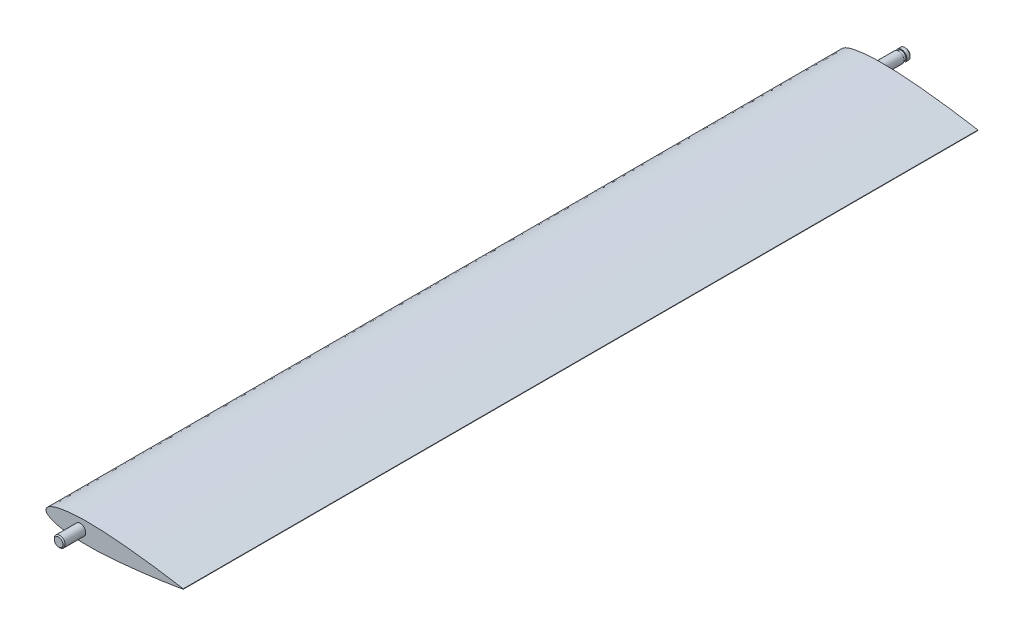
SolidWorks part; units mm, degrees
material "AISI Carbon Fiber"
ref_plane "Front Plane" through (0, 0, 0) normal (0, 0, 1) x (1, 0, 0)
ref_plane "Top Plane" through (0, 0, 0) normal (0, 1, 0) x (1, 0, 0)
ref_plane "Right Plane" through (0, 0, 0) normal (1, 0, 0) x (0, 0, -1)
curve "Curve1"
  spline degree 3 poles (38, 0.0599, 0) (37.987, 0.0621, 0) (37.935, 0.0712, 0) (37.8182, 0.0917, 0) (37.6241, 0.1254, 0) (37.3535, 0.1721, 0) (37.0074, 0.2313, 0) (36.5874, 0.3022, 0) (36.0951, 0.3842, 0) (35.5325, 0.4763, 0) (34.902, 0.5776, 0) (34.2062, 0.6871, 0) (33.4479, 0.8039, 0) (32.6302, 0.9268, 0) (31.7565, 1.0547, 0) (30.8304, 1.1867, 0) (29.8556, 1.3214, 0) (28.8363, 1.4579, 0) (27.7765, 1.595, 0) (26.6807, 1.7315, 0) (25.5533, 1.8661, 0) (24.399, 1.9977, 0) (23.2225, 2.125, 0) (22.0286, 2.2465, 0) (20.8224, 2.361, 0) (19.6086, 2.467, 0) (18.3923, 2.5631, 0) (17.1785, 2.6478, 0) (15.9721, 2.7198, 0) (14.7782, 2.7776, 0) (13.6016, 2.82, 0) (12.4472, 2.8458, 0) (11.3196, 2.8539, 0) (10.2236, 2.8435, 0) (9.1636, 2.8139, 0) (8.144, 2.7648, 0) (7.1689, 2.6959, 0) (6.2424, 2.6073, 0) (5.3682, 2.4992, 0) (4.55, 2.3724, 0) (3.7909, 2.2275, 0) (3.0942, 2.0654, 0) (2.4625, 1.8874, 0) (1.8984, 1.6945, 0) (1.4039, 1.4881, 0) (0.9808, 1.2692, 0) (0.6303, 1.0387, 0) (0.3535, 0.7969, 0) (0.1517, 0.5431, 0) (0.0276, 0.2761, 0) (-0.0134, 0, 0) (0.0276, -0.2761, 0) (0.1517, -0.5431, 0) (0.3535, -0.7969, 0) (0.6303, -1.0387, 0) (0.9808, -1.2692, 0) (1.4039, -1.4881, 0) (1.8984, -1.6945, 0) (2.4625, -1.8874, 0) (3.0942, -2.0654, 0) (3.7909, -2.2275, 0) (4.55, -2.3724, 0) (5.3682, -2.4992, 0) (6.2424, -2.6073, 0) (7.1689, -2.6959, 0) (8.144, -2.7648, 0) (9.1636, -2.8139, 0) (10.2236, -2.8435, 0) (11.3196, -2.8539, 0) (12.4472, -2.8458, 0) (13.6016, -2.82, 0) (14.7782, -2.7776, 0) (15.9721, -2.7198, 0) (17.1785, -2.6478, 0) (18.3923, -2.5631, 0) (19.6086, -2.467, 0) (20.8224, -2.361, 0) (22.0286, -2.2465, 0) (23.2225, -2.125, 0) (24.399, -1.9977, 0) (25.5533, -1.8661, 0) (26.6807, -1.7315, 0) (27.7765, -1.595, 0) (28.8363, -1.4579, 0) (29.8556, -1.3214, 0) (30.8304, -1.1867, 0) (31.7565, -1.0547, 0) (32.6302, -0.9268, 0) (33.4479, -0.8039, 0) (34.2062, -0.6871, 0) (34.902, -0.5776, 0) (35.5325, -0.4763, 0) (36.0951, -0.3842, 0) (36.5874, -0.3022, 0) (37.0074, -0.2313, 0) (37.3535, -0.1721, 0) (37.6241, -0.1254, 0) (37.8182, -0.0917, 0) (37.935, -0.0712, 0) (37.987, -0.0621, 0) (38, -0.0599, 0) knots 0 0 0 0 0.000507 0.002027 0.004551 0.008071 0.01257 0.018029 0.024425 0.031731 0.039914 0.048941 0.058774 0.06937 0.080686 0.092674 0.105284 0.118464 0.132158 0.146309 0.160859 0.175747 0.190912 0.20629 0.221818 0.237431 0.253066 0.268658 0.284144 0.299461 0.314547 0.329343 0.343791 0.357834 0.37142 0.384499 0.397022 0.408945 0.420228 0.430833 0.440729 0.449888 0.458288 0.465915 0.472763 0.478842 0.484178 0.488829 0.492895 0.49654 0.5 0.50346 0.507105 0.511171 0.515822 0.521158 0.527237 0.534085 0.541712 0.550112 0.559271 0.569167 0.579772 0.591055 0.602978 0.615501 0.62858 0.642166 0.656209 0.670657 0.685453 0.700539 0.715856 0.731342 0.746934 0.762569 0.778182 0.79371 0.809088 0.824253 0.839141 0.853691 0.867842 0.881536 0.894716 0.907326 0.919314 0.93063 0.941226 0.951059 0.960086 0.968269 0.975575 0.981971 0.98743 0.991929 0.995449 0.997973 0.999493 1 1 1 1
sketch3d "3DSketch1"
  line L0 (0, 0, 0) -> (38, 0, 0) construction
  line L1 (9.5, -5.7646, 0) -> (9.5, 5.7646, 0) construction
  line L2 (38, 0.0599, 0) -> (38, -0.0599, 0)
  spline S0 degree 3 poles (604.1581, 2945.7624, 0) (69.9098, -7.9846, 0) (54.106, -2.7558, 0) (37.1208, 0.2136, 0) (35.8767, 0.4227, 0) (34.1443, 0.698, 0) (32.8836, 0.8897, 0) (31.7565, 1.0547, 0) (30.8304, 1.1867, 0) (29.8556, 1.3214, 0) (28.8363, 1.4579, 0) (27.7765, 1.595, 0) (26.6807, 1.7315, 0) (25.5533, 1.8661, 0) (24.399, 1.9977, 0) (23.2225, 2.125, 0) (22.0286, 2.2465, 0) (20.8224, 2.361, 0) (19.6086, 2.467, 0) (18.3923, 2.5631, 0) (17.1785, 2.6478, 0) (15.9721, 2.7198, 0) (14.7782, 2.7776, 0) (13.6016, 2.82, 0) (12.4472, 2.8458, 0) (11.3196, 2.8539, 0) (10.2236, 2.8435, 0) (9.1636, 2.8139, 0) (8.144, 2.7648, 0) (7.1689, 2.6959, 0) (6.2424, 2.6073, 0) (5.3682, 2.4992, 0) (4.55, 2.3724, 0) (3.7909, 2.2275, 0) (3.0942, 2.0654, 0) (2.4625, 1.8874, 0) (1.8984, 1.6945, 0) (1.4039, 1.4881, 0) (0.9808, 1.2692, 0) (0.6303, 1.0387, 0) (0.3535, 0.7969, 0) (0.1517, 0.5431, 0) (0.0276, 0.2761, 0) (-0.0134, 0, 0) (0.0276, -0.2761, 0) (0.1517, -0.5431, 0) (0.3535, -0.7969, 0) (0.6303, -1.0387, 0) (0.9808, -1.2692, 0) (1.4039, -1.4881, 0) (1.8984, -1.6945, 0) (2.4625, -1.8874, 0) (3.0942, -2.0654, 0) (3.7909, -2.2275, 0) (4.55, -2.3724, 0) (5.3682, -2.4992, 0) (6.2424, -2.6073, 0) (7.1689, -2.6959, 0) (8.144, -2.7648, 0) (9.1636, -2.8139, 0) (10.2236, -2.8435, 0) (11.3196, -2.8539, 0) (12.4472, -2.8458, 0) (13.6016, -2.82, 0) (14.7782, -2.7776, 0) (15.9721, -2.7198, 0) (17.1785, -2.6478, 0) (18.3923, -2.5631, 0) (19.6086, -2.467, 0) (20.8224, -2.361, 0) (22.0286, -2.2465, 0) (23.2225, -2.125, 0) (24.399, -1.9977, 0) (25.5533, -1.8661, 0) (26.6807, -1.7315, 0) (27.7765, -1.595, 0) (28.8363, -1.4579, 0) (29.8556, -1.3214, 0) (30.8304, -1.1867, 0) (32.0297, -1.0158, 0) (33.3891, -0.8142, 0) (34.8372, -0.589, 0) (36.1409, -0.3777, 0) (37.0492, -0.2247, 0) (37.6241, -0.1254, 0) (37.8182, -0.0917, 0) (54.1059, 2.7557, 0) (69.9096, 7.9845, 0) (604.1475, -2945.7032, 0) knots -0.630247 -0.630247 -0.630247 -0.630247 0.000507 0.002027 0.031731 0.048941 0.06937 0.080686 0.092674 0.105284 0.118464 0.132158 0.146309 0.160859 0.175747 0.190912 0.20629 0.221818 0.237431 0.253066 0.268658 0.284144 0.299461 0.314547 0.329343 0.343791 0.357834 0.37142 0.384499 0.397022 0.408945 0.420228 0.430833 0.440729 0.449888 0.458288 0.465915 0.472763 0.478842 0.484178 0.488829 0.492895 0.49654 0.5 0.50346 0.507105 0.511171 0.515822 0.521158 0.527237 0.534085 0.541712 0.550112 0.559271 0.569167 0.579772 0.591055 0.602978 0.615501 0.62858 0.642166 0.656209 0.670657 0.685453 0.700539 0.715856 0.731342 0.746934 0.762569 0.778182 0.79371 0.809088 0.824253 0.839141 0.853691 0.867842 0.881536 0.894716 0.907326 0.919314 0.941226 0.960086 0.975575 0.991929 0.995449 0.997973 0.999493 1.630243 1.630243 1.630243 1.630243 only from (38, 0.0599, 0) to (38, -0.0599, 0) construction
  spline S1 degree 3 poles (38, 0.0599, 0) (37.987, 0.0621, 0) (37.935, 0.0712, 0) (37.1208, 0.2136, 0) (35.8767, 0.4227, 0) (34.1443, 0.698, 0) (32.8836, 0.8897, 0) (31.7565, 1.0547, 0) (30.8304, 1.1867, 0) (29.8556, 1.3214, 0) (28.8363, 1.4579, 0) (27.7765, 1.595, 0) (26.6807, 1.7315, 0) (25.5533, 1.8661, 0) (24.399, 1.9977, 0) (23.2225, 2.125, 0) (22.0286, 2.2465, 0) (20.8224, 2.361, 0) (19.6086, 2.467, 0) (18.3923, 2.5631, 0) (17.1785, 2.6478, 0) (15.9721, 2.7198, 0) (14.7782, 2.7776, 0) (13.6016, 2.82, 0) (12.4472, 2.8458, 0) (11.3196, 2.8539, 0) (10.2236, 2.8435, 0) (9.1636, 2.8139, 0) (8.144, 2.7648, 0) (7.1689, 2.6959, 0) (6.2424, 2.6073, 0) (5.3682, 2.4992, 0) (4.55, 2.3724, 0) (3.7909, 2.2275, 0) (3.0942, 2.0654, 0) (2.4625, 1.8874, 0) (1.8984, 1.6945, 0) (1.4039, 1.4881, 0) (0.9808, 1.2692, 0) (0.6303, 1.0387, 0) (0.3535, 0.7969, 0) (0.1517, 0.5431, 0) (0.0276, 0.2761, 0) (-0.0134, 0, 0) (0.0276, -0.2761, 0) (0.1517, -0.5431, 0) (0.3535, -0.7969, 0) (0.6303, -1.0387, 0) (0.9808, -1.2692, 0) (1.4039, -1.4881, 0) (1.8984, -1.6945, 0) (2.4625, -1.8874, 0) (3.0942, -2.0654, 0) (3.7909, -2.2275, 0) (4.55, -2.3724, 0) (5.3682, -2.4992, 0) (6.2424, -2.6073, 0) (7.1689, -2.6959, 0) (8.144, -2.7648, 0) (9.1636, -2.8139, 0) (10.2236, -2.8435, 0) (11.3196, -2.8539, 0) (12.4472, -2.8458, 0) (13.6016, -2.82, 0) (14.7782, -2.7776, 0) (15.9721, -2.7198, 0) (17.1785, -2.6478, 0) (18.3923, -2.5631, 0) (19.6086, -2.467, 0) (20.8224, -2.361, 0) (22.0286, -2.2465, 0) (23.2225, -2.125, 0) (24.399, -1.9977, 0) (25.5533, -1.8661, 0) (26.6807, -1.7315, 0) (27.7765, -1.595, 0) (28.8363, -1.4579, 0) (29.8556, -1.3214, 0) (30.8304, -1.1867, 0) (32.0297, -1.0158, 0) (33.3891, -0.8142, 0) (34.8372, -0.589, 0) (36.1409, -0.3777, 0) (37.0492, -0.2247, 0) (37.6241, -0.1254, 0) (37.8182, -0.0917, 0) (37.935, -0.0712, 0) (37.987, -0.0621, 0) (38, -0.0599, 0) knots 0 0 0 0 0.000507 0.002027 0.031731 0.048941 0.06937 0.080686 0.092674 0.105284 0.118464 0.132158 0.146309 0.160859 0.175747 0.190912 0.20629 0.221818 0.237431 0.253066 0.268658 0.284144 0.299461 0.314547 0.329343 0.343791 0.357834 0.37142 0.384499 0.397022 0.408945 0.420228 0.430833 0.440729 0.449888 0.458288 0.465915 0.472763 0.478842 0.484178 0.488829 0.492895 0.49654 0.5 0.50346 0.507105 0.511171 0.515822 0.521158 0.527237 0.534085 0.541712 0.550112 0.559271 0.569167 0.579772 0.591055 0.602978 0.615501 0.62858 0.642166 0.656209 0.670657 0.685453 0.700539 0.715856 0.731342 0.746934 0.762569 0.778182 0.79371 0.809088 0.824253 0.839141 0.853691 0.867842 0.881536 0.894716 0.907326 0.919314 0.941226 0.960086 0.975575 0.991929 0.995449 0.997973 0.999493 1 1 1 1
  point P8 (9.5, 0, 0)
  dimension "D1" = 0.1197
extrude "Boss-Extrude1" add sketch "3DSketch1" along direction (0, 0, 1) on the side of the normal blind 220
curve "Curve6"
  spline degree 3 poles (0.8371, 0.1076, 0) (0.8458, 0.1212, 0) (0.8686, 0.1567, 0) (0.9123, 0.2091, 0) (0.9749, 0.2742, 0) (1.0496, 0.3405, 0) (1.148, 0.4173, 0) (1.2564, 0.4919, 0) (1.3911, 0.5748, 0) (1.5328, 0.6532, 0) (1.7028, 0.7383, 0) (1.8766, 0.8172, 0) (2.0803, 0.9017, 0) (2.3018, 0.9855, 0) (2.5379, 1.0666, 0) (2.7908, 1.1464, 0) (3.0397, 1.2184, 0) (3.3223, 1.2936, 0) (3.598, 1.3609, 0) (3.9088, 1.4305, 0) (4.21, 1.4924, 0) (4.5476, 1.5559, 0) (4.8731, 1.6117, 0) (5.236, 1.6684, 0) (5.6124, 1.7217, 0) (5.9994, 1.7707, 0) (6.399, 1.8161, 0) (6.7803, 1.8548, 0) (7.2016, 1.8926, 0) (7.6023, 1.9241, 0) (8.0438, 1.9542, 0) (8.4627, 1.9784, 0) (8.9229, 2.0006, 0) (9.3583, 2.0176, 0) (9.8356, 2.032, 0) (10.3217, 2.0426, 0) (10.8145, 2.0489, 0) (11.3152, 2.0514, 0) (11.7864, 2.0503, 0) (12.3, 2.0454, 0) (12.7823, 2.0376, 0) (13.3071, 2.0257, 0) (13.7991, 2.0114, 0) (14.3334, 1.9928, 0) (14.8333, 1.9726, 0) (15.3753, 1.9476, 0) (15.9208, 1.9197, 0) (16.4687, 1.8886, 0) (17.0192, 1.8548, 0) (17.532, 1.8209, 0) (18.0855, 1.782, 0) (18.6004, 1.7436, 0) (19.1552, 1.7001, 0) (19.6704, 1.6577, 0) (20.2247, 1.6101, 0) (20.7386, 1.5641, 0) (21.2905, 1.5129, 0) (21.8404, 1.4601, 0) (22.3882, 1.4056, 0) (22.933, 1.3499, 0) (23.4358, 1.2969, 0) (23.9736, 1.2389, 0) (24.4692, 1.184, 0) (24.9983, 1.1241, 0) (25.485, 1.0678, 0) (26.0037, 1.0066, 0) (26.4799, 0.9493, 0) (26.9865, 0.8871, 0) (27.4857, 0.8248, 0) (27.9785, 0.762, 0) (28.463, 0.6994, 0) (28.9056, 0.6412, 0) (29.3739, 0.5787, 0) (29.8006, 0.5209, 0) (30.2512, 0.4591, 0) (30.6608, 0.4021, 0) (31.0922, 0.3412, 0) (31.4833, 0.2853, 0) (31.8941, 0.2259, 0) (32.2929, 0.1676, 0) (32.5742, 0.1257, 0) (32.7126, 0.1052, 0) knots 0 0 0 0 0.001498 0.003915 0.006305 0.009868 0.013175 0.01787 0.022065 0.027843 0.032883 0.039693 0.045539 0.053333 0.061655 0.068685 0.077928 0.085679 0.095804 0.104247 0.115218 0.124322 0.136103 0.145839 0.158391 0.171355 0.182014 0.195688 0.2069 0.221242 0.232971 0.24794 0.260151 0.275699 0.288356 0.304436 0.320791 0.334062 0.350872 0.364486 0.381697 0.395612 0.413171 0.427341 0.445193 0.459574 0.477661 0.495853 0.51047 0.528806 0.543514 0.561934 0.576686 0.59513 0.609876 0.628283 0.642977 0.661287 0.679517 0.694031 0.712071 0.726408 0.744198 0.758312 0.775793 0.789637 0.806751 0.82028 0.836971 0.853405 0.866354 0.88228 0.894802 0.910169 0.922223 0.936979 0.948526 0.962623 0.973625 0.987018 1 1 1 1
curve "Curve7"
  spline degree 3 poles (0.8371, -0.1076, 0) (0.8458, -0.1212, 0) (0.8686, -0.1567, 0) (0.9123, -0.2091, 0) (0.9749, -0.2742, 0) (1.0496, -0.3405, 0) (1.148, -0.4173, 0) (1.2564, -0.4919, 0) (1.3911, -0.5748, 0) (1.5328, -0.6532, 0) (1.7028, -0.7383, 0) (1.8766, -0.8172, 0) (2.0803, -0.9017, 0) (2.3018, -0.9855, 0) (2.5379, -1.0666, 0) (2.7908, -1.1464, 0) (3.0397, -1.2184, 0) (3.3223, -1.2936, 0) (3.598, -1.3609, 0) (3.9088, -1.4305, 0) (4.21, -1.4924, 0) (4.5476, -1.5559, 0) (4.8731, -1.6117, 0) (5.236, -1.6684, 0) (5.6124, -1.7217, 0) (5.9994, -1.7707, 0) (6.399, -1.8161, 0) (6.7803, -1.8548, 0) (7.2016, -1.8926, 0) (7.6023, -1.9241, 0) (8.0438, -1.9542, 0) (8.4627, -1.9784, 0) (8.9229, -2.0006, 0) (9.3583, -2.0176, 0) (9.8356, -2.032, 0) (10.3217, -2.0426, 0) (10.8145, -2.0489, 0) (11.3152, -2.0514, 0) (11.7864, -2.0503, 0) (12.3, -2.0454, 0) (12.7823, -2.0376, 0) (13.3071, -2.0257, 0) (13.7991, -2.0114, 0) (14.3334, -1.9928, 0) (14.8333, -1.9726, 0) (15.3753, -1.9476, 0) (15.9208, -1.9197, 0) (16.4687, -1.8886, 0) (17.0192, -1.8548, 0) (17.532, -1.8209, 0) (18.0855, -1.782, 0) (18.6004, -1.7436, 0) (19.1552, -1.7001, 0) (19.6704, -1.6577, 0) (20.2247, -1.6101, 0) (20.7386, -1.5641, 0) (21.2905, -1.5129, 0) (21.8404, -1.4601, 0) (22.3882, -1.4056, 0) (22.933, -1.3499, 0) (23.4358, -1.2969, 0) (23.9736, -1.2389, 0) (24.4692, -1.184, 0) (24.9983, -1.1241, 0) (25.485, -1.0678, 0) (26.0037, -1.0066, 0) (26.4799, -0.9493, 0) (26.9865, -0.8871, 0) (27.4857, -0.8248, 0) (27.9785, -0.762, 0) (28.463, -0.6994, 0) (28.9056, -0.6412, 0) (29.3739, -0.5787, 0) (29.8006, -0.5209, 0) (30.2512, -0.4591, 0) (30.6608, -0.4021, 0) (31.0922, -0.3412, 0) (31.4833, -0.2853, 0) (31.8941, -0.2259, 0) (32.2929, -0.1676, 0) (32.5742, -0.1257, 0) (32.7126, -0.1052, 0) knots 0 0 0 0 0.001498 0.003915 0.006305 0.009868 0.013175 0.01787 0.022065 0.027843 0.032883 0.039693 0.045539 0.053333 0.061655 0.068685 0.077928 0.085679 0.095804 0.104247 0.115218 0.124322 0.136103 0.145839 0.158391 0.171355 0.182014 0.195688 0.2069 0.221242 0.232971 0.24794 0.260151 0.275699 0.288356 0.304436 0.320791 0.334062 0.350872 0.364486 0.381697 0.395612 0.413171 0.427341 0.445193 0.459574 0.477661 0.495853 0.51047 0.528806 0.543514 0.561934 0.576686 0.59513 0.609876 0.628283 0.642977 0.661287 0.679517 0.694031 0.712071 0.726408 0.744198 0.758312 0.775793 0.789637 0.806751 0.82028 0.836971 0.853405 0.866354 0.88228 0.894802 0.910169 0.922223 0.936979 0.948526 0.962623 0.973625 0.987018 1 1 1 1
sketch "Sketch5" plane through (0, 0, 0) normal (0, 0, -1) x (-1, 0, 0)
  line L0 (-32.7126, 0.1052) -> (-32.7126, -0.1052)
  line L1 (-38, 0.0599) -> (-38, -0.0599)
  line L2 (-38, 0.0599) -> (-38, -0.0599)
  line L3 (-0.8371, 0.1076) -> (-0.8371, -0.1076)
  spline S0 degree 3 poles (4087.6061, -2873.0002) (-19.499, 20.4027) (1.0641, 2.163) (-0.9123, -0.2091) (-0.9749, -0.2742) (-1.0496, -0.3405) (-1.148, -0.4173) (-1.2564, -0.4919) (-1.3911, -0.5748) (-1.5328, -0.6532) (-1.7028, -0.7383) (-1.8766, -0.8172) (-2.0803, -0.9017) (-2.3018, -0.9855) (-2.5379, -1.0666) (-2.7908, -1.1464) (-3.0397, -1.2184) (-3.3223, -1.2936) (-3.598, -1.3609) (-3.9088, -1.4305) (-4.21, -1.4924) (-4.5476, -1.5559) (-4.8731, -1.6117) (-5.236, -1.6684) (-5.6124, -1.7217) (-5.9994, -1.7707) (-6.399, -1.8161) (-6.7803, -1.8548) (-7.2016, -1.8926) (-7.6023, -1.9241) (-8.0438, -1.9542) (-8.6301, -1.9881) (-9.2267, -2.0137) (-10.0119, -2.0374) (-10.6411, -2.048) (-11.462, -2.0521) (-12.2688, -2.0475) (-13.2744, -2.0281) (-14.2992, -1.9956) (-15.1831, -1.9575) (-16.0782, -1.9116) (-16.9818, -1.8584) (-18.0471, -1.7859) (-19.1158, -1.7043) (-20.1845, -1.6145) (-21.2887, -1.5141) (-22.5393, -1.3918) (-23.7761, -1.2615) (-24.9561, -1.1296) (-26.1402, -0.9913) (-27.4669, -0.8286) (-28.8848, -0.6452) (-30.0767, -0.4838) (-30.9347, -0.3637) (-31.4833, -0.2853) (-31.8941, -0.2259) (-75.5916, 6.1667) (-116.8044, 28.5604) (-893.0755, -4923.7281) knots -0.279234 -0.279234 -0.279234 -0.279234 0.001498 0.003915 0.006305 0.009868 0.013175 0.01787 0.022065 0.027843 0.032883 0.039693 0.045539 0.053333 0.061655 0.068685 0.077928 0.085679 0.095804 0.104247 0.115218 0.124322 0.136103 0.145839 0.158391 0.171355 0.182014 0.195688 0.2069 0.221242 0.232971 0.24794 0.275699 0.288356 0.320791 0.334062 0.364486 0.395612 0.427341 0.459574 0.477661 0.51047 0.543514 0.576686 0.609876 0.642977 0.679517 0.726408 0.758312 0.789637 0.836971 0.88228 0.922223 0.948526 0.962623 0.973625 0.987018 5.058378 5.058378 5.058378 5.058378 only from (-0.8371, -0.1076) to (-32.7126, -0.1052) construction
  spline S1 degree 3 poles (-1134.4373, -5897.8795) (-78.0711, 10.8547) (-58.3094, 3.4906) (-37.8182, -0.0917) (-37.6241, -0.1254) (-37.0492, -0.2247) (-36.1409, -0.3777) (-34.8372, -0.589) (-33.3891, -0.8142) (-32.0297, -1.0158) (-30.8304, -1.1867) (-29.8556, -1.3214) (-28.8363, -1.4579) (-27.7765, -1.595) (-26.6807, -1.7315) (-25.5533, -1.8661) (-24.399, -1.9977) (-23.2225, -2.125) (-22.0286, -2.2465) (-20.8224, -2.361) (-19.6086, -2.467) (-18.3923, -2.5631) (-17.1785, -2.6478) (-15.9721, -2.7198) (-14.7782, -2.7776) (-13.6016, -2.82) (-12.4472, -2.8458) (-11.3196, -2.8539) (-10.2236, -2.8435) (-9.1636, -2.8139) (-8.144, -2.7648) (-7.1689, -2.6959) (-6.2424, -2.6073) (-5.3682, -2.4992) (-4.55, -2.3724) (-3.7909, -2.2275) (-3.0942, -2.0654) (-2.4625, -1.8874) (-1.8984, -1.6945) (-1.4039, -1.4881) (-0.9808, -1.2692) (-0.6303, -1.0387) (-0.3535, -0.7969) (-0.1517, -0.5431) (-0.0276, -0.2761) (0.0134, 0) (-0.0276, 0.2761) (-0.1517, 0.5431) (-0.3535, 0.7969) (-0.6303, 1.0387) (-0.9808, 1.2692) (-1.4039, 1.4881) (-1.8984, 1.6945) (-2.4625, 1.8874) (-3.0942, 2.0654) (-3.7909, 2.2275) (-4.55, 2.3724) (-5.3682, 2.4992) (-6.2424, 2.6073) (-7.1689, 2.6959) (-8.144, 2.7648) (-9.1636, 2.8139) (-10.2236, 2.8435) (-11.3196, 2.8539) (-12.4472, 2.8458) (-13.6016, 2.82) (-14.7782, 2.7776) (-15.9721, 2.7198) (-17.1785, 2.6478) (-18.3923, 2.5631) (-19.6086, 2.467) (-20.8224, 2.361) (-22.0286, 2.2465) (-23.2225, 2.125) (-24.399, 1.9977) (-25.5533, 1.8661) (-26.6807, 1.7315) (-27.7765, 1.595) (-28.8363, 1.4579) (-29.8556, 1.3214) (-30.8304, 1.1867) (-31.7565, 1.0547) (-32.8836, 0.8897) (-34.1443, 0.698) (-35.8767, 0.4227) (-37.1208, 0.2136) (-58.3096, -3.4906) (-78.0715, -10.8549) (-1134.4729, 5898.0786) knots -0.794067 -0.794067 -0.794067 -0.794067 0.000507 0.002027 0.004551 0.008071 0.024425 0.039914 0.058774 0.080686 0.092674 0.105284 0.118464 0.132158 0.146309 0.160859 0.175747 0.190912 0.20629 0.221818 0.237431 0.253066 0.268658 0.284144 0.299461 0.314547 0.329343 0.343791 0.357834 0.37142 0.384499 0.397022 0.408945 0.420228 0.430833 0.440729 0.449888 0.458288 0.465915 0.472763 0.478842 0.484178 0.488829 0.492895 0.49654 0.5 0.50346 0.507105 0.511171 0.515822 0.521158 0.527237 0.534085 0.541712 0.550112 0.559271 0.569167 0.579772 0.591055 0.602978 0.615501 0.62858 0.642166 0.656209 0.670657 0.685453 0.700539 0.715856 0.731342 0.746934 0.762569 0.778182 0.79371 0.809088 0.824253 0.839141 0.853691 0.867842 0.881536 0.894716 0.907326 0.919314 0.93063 0.951059 0.968269 0.997973 0.999493 1.794076 1.794076 1.794076 1.794076 only from (-38, -0.0599) to (-38, 0.0599)
  spline S2 degree 3 poles (-38, -0.0599) (-37.987, -0.0621) (-37.935, -0.0712) (-37.8182, -0.0917) (-37.6241, -0.1254) (-37.0492, -0.2247) (-36.1409, -0.3777) (-34.8372, -0.589) (-33.3891, -0.8142) (-32.0297, -1.0158) (-30.8304, -1.1867) (-29.8556, -1.3214) (-28.8363, -1.4579) (-27.7765, -1.595) (-26.6807, -1.7315) (-25.5533, -1.8661) (-24.399, -1.9977) (-23.2225, -2.125) (-22.0286, -2.2465) (-20.8224, -2.361) (-19.6086, -2.467) (-18.3923, -2.5631) (-17.1785, -2.6478) (-15.9721, -2.7198) (-14.7782, -2.7776) (-13.6016, -2.82) (-12.4472, -2.8458) (-11.3196, -2.8539) (-10.2236, -2.8435) (-9.1636, -2.8139) (-8.144, -2.7648) (-7.1689, -2.6959) (-6.2424, -2.6073) (-5.3682, -2.4992) (-4.55, -2.3724) (-3.7909, -2.2275) (-3.0942, -2.0654) (-2.4625, -1.8874) (-1.8984, -1.6945) (-1.4039, -1.4881) (-0.9808, -1.2692) (-0.6303, -1.0387) (-0.3535, -0.7969) (-0.1517, -0.5431) (-0.0276, -0.2761) (0.0134, 0) (-0.0276, 0.2761) (-0.1517, 0.5431) (-0.3535, 0.7969) (-0.6303, 1.0387) (-0.9808, 1.2692) (-1.4039, 1.4881) (-1.8984, 1.6945) (-2.4625, 1.8874) (-3.0942, 2.0654) (-3.7909, 2.2275) (-4.55, 2.3724) (-5.3682, 2.4992) (-6.2424, 2.6073) (-7.1689, 2.6959) (-8.144, 2.7648) (-9.1636, 2.8139) (-10.2236, 2.8435) (-11.3196, 2.8539) (-12.4472, 2.8458) (-13.6016, 2.82) (-14.7782, 2.7776) (-15.9721, 2.7198) (-17.1785, 2.6478) (-18.3923, 2.5631) (-19.6086, 2.467) (-20.8224, 2.361) (-22.0286, 2.2465) (-23.2225, 2.125) (-24.399, 1.9977) (-25.5533, 1.8661) (-26.6807, 1.7315) (-27.7765, 1.595) (-28.8363, 1.4579) (-29.8556, 1.3214) (-30.8304, 1.1867) (-31.7565, 1.0547) (-32.8836, 0.8897) (-34.1443, 0.698) (-35.8767, 0.4227) (-37.1208, 0.2136) (-37.935, 0.0712) (-37.987, 0.0621) (-38, 0.0599) knots 0 0 0 0 0.000507 0.002027 0.004551 0.008071 0.024425 0.039914 0.058774 0.080686 0.092674 0.105284 0.118464 0.132158 0.146309 0.160859 0.175747 0.190912 0.20629 0.221818 0.237431 0.253066 0.268658 0.284144 0.299461 0.314547 0.329343 0.343791 0.357834 0.37142 0.384499 0.397022 0.408945 0.420228 0.430833 0.440729 0.449888 0.458288 0.465915 0.472763 0.478842 0.484178 0.488829 0.492895 0.49654 0.5 0.50346 0.507105 0.511171 0.515822 0.521158 0.527237 0.534085 0.541712 0.550112 0.559271 0.569167 0.579772 0.591055 0.602978 0.615501 0.62858 0.642166 0.656209 0.670657 0.685453 0.700539 0.715856 0.731342 0.746934 0.762569 0.778182 0.79371 0.809088 0.824253 0.839141 0.853691 0.867842 0.881536 0.894716 0.907326 0.919314 0.93063 0.951059 0.968269 0.997973 0.999493 1 1 1 1
  spline S3 degree 3 poles (4087.6061, 2873.0002) (-19.499, -20.4027) (1.0641, -2.163) (-0.9123, 0.2091) (-0.9749, 0.2742) (-1.0496, 0.3405) (-1.148, 0.4173) (-1.2564, 0.4919) (-1.3911, 0.5748) (-1.5328, 0.6532) (-1.7028, 0.7383) (-1.8766, 0.8172) (-2.0803, 0.9017) (-2.3018, 0.9855) (-2.5379, 1.0666) (-2.7908, 1.1464) (-3.0397, 1.2184) (-3.3223, 1.2936) (-3.598, 1.3609) (-3.9088, 1.4305) (-4.21, 1.4924) (-4.5476, 1.5559) (-4.8731, 1.6117) (-5.236, 1.6684) (-5.6124, 1.7217) (-5.9994, 1.7707) (-6.399, 1.8161) (-6.7803, 1.8548) (-7.2016, 1.8926) (-7.6023, 1.9241) (-8.0438, 1.9542) (-8.6301, 1.9881) (-9.2267, 2.0137) (-10.0119, 2.0374) (-10.6411, 2.048) (-11.462, 2.0521) (-12.2688, 2.0475) (-13.2744, 2.0281) (-14.2992, 1.9956) (-15.1831, 1.9575) (-16.0782, 1.9116) (-16.9818, 1.8584) (-18.0471, 1.7859) (-19.1158, 1.7043) (-20.1845, 1.6145) (-21.2887, 1.5141) (-22.5393, 1.3918) (-23.7761, 1.2615) (-24.9561, 1.1296) (-26.1402, 0.9913) (-27.4669, 0.8286) (-28.8848, 0.6452) (-30.0767, 0.4838) (-30.9347, 0.3637) (-31.4833, 0.2853) (-31.8941, 0.2259) (-75.5916, -6.1667) (-116.8044, -28.5604) (-893.0755, 4923.7281) knots -0.279234 -0.279234 -0.279234 -0.279234 0.001498 0.003915 0.006305 0.009868 0.013175 0.01787 0.022065 0.027843 0.032883 0.039693 0.045539 0.053333 0.061655 0.068685 0.077928 0.085679 0.095804 0.104247 0.115218 0.124322 0.136103 0.145839 0.158391 0.171355 0.182014 0.195688 0.2069 0.221242 0.232971 0.24794 0.275699 0.288356 0.320791 0.334062 0.364486 0.395612 0.427341 0.459574 0.477661 0.51047 0.543514 0.576686 0.609876 0.642977 0.679517 0.726408 0.758312 0.789637 0.836971 0.88228 0.922223 0.948526 0.962623 0.973625 0.987018 5.058378 5.058378 5.058378 5.058378 only from (-0.8371, 0.1076) to (-32.7126, 0.1052) construction
  spline S4 degree 3 poles (-0.8371, -0.1076) (-0.8458, -0.1212) (-0.8686, -0.1567) (-0.9123, -0.2091) (-0.9749, -0.2742) (-1.0496, -0.3405) (-1.148, -0.4173) (-1.2564, -0.4919) (-1.3911, -0.5748) (-1.5328, -0.6532) (-1.7028, -0.7383) (-1.8766, -0.8172) (-2.0803, -0.9017) (-2.3018, -0.9855) (-2.5379, -1.0666) (-2.7908, -1.1464) (-3.0397, -1.2184) (-3.3223, -1.2936) (-3.598, -1.3609) (-3.9088, -1.4305) (-4.21, -1.4924) (-4.5476, -1.5559) (-4.8731, -1.6117) (-5.236, -1.6684) (-5.6124, -1.7217) (-5.9994, -1.7707) (-6.399, -1.8161) (-6.7803, -1.8548) (-7.2016, -1.8926) (-7.6023, -1.9241) (-8.0438, -1.9542) (-8.6301, -1.9881) (-9.2267, -2.0137) (-10.0119, -2.0374) (-10.6411, -2.048) (-11.462, -2.0521) (-12.2688, -2.0475) (-13.2744, -2.0281) (-14.2992, -1.9956) (-15.1831, -1.9575) (-16.0782, -1.9116) (-16.9818, -1.8584) (-18.0471, -1.7859) (-19.1158, -1.7043) (-20.1845, -1.6145) (-21.2887, -1.5141) (-22.5393, -1.3918) (-23.7761, -1.2615) (-24.9561, -1.1296) (-26.1402, -0.9913) (-27.4669, -0.8286) (-28.8848, -0.6452) (-30.0767, -0.4838) (-30.9347, -0.3637) (-31.4833, -0.2853) (-31.8941, -0.2259) (-32.2929, -0.1676) (-32.5742, -0.1257) (-32.7126, -0.1052) knots 0 0 0 0 0.001498 0.003915 0.006305 0.009868 0.013175 0.01787 0.022065 0.027843 0.032883 0.039693 0.045539 0.053333 0.061655 0.068685 0.077928 0.085679 0.095804 0.104247 0.115218 0.124322 0.136103 0.145839 0.158391 0.171355 0.182014 0.195688 0.2069 0.221242 0.232971 0.24794 0.275699 0.288356 0.320791 0.334062 0.364486 0.395612 0.427341 0.459574 0.477661 0.51047 0.543514 0.576686 0.609876 0.642977 0.679517 0.726408 0.758312 0.789637 0.836971 0.88228 0.922223 0.948526 0.962623 0.973625 0.987018 1 1 1 1
  spline S5 degree 3 poles (-0.8371, 0.1076) (-0.8458, 0.1212) (-0.8686, 0.1567) (-0.9123, 0.2091) (-0.9749, 0.2742) (-1.0496, 0.3405) (-1.148, 0.4173) (-1.2564, 0.4919) (-1.3911, 0.5748) (-1.5328, 0.6532) (-1.7028, 0.7383) (-1.8766, 0.8172) (-2.0803, 0.9017) (-2.3018, 0.9855) (-2.5379, 1.0666) (-2.7908, 1.1464) (-3.0397, 1.2184) (-3.3223, 1.2936) (-3.598, 1.3609) (-3.9088, 1.4305) (-4.21, 1.4924) (-4.5476, 1.5559) (-4.8731, 1.6117) (-5.236, 1.6684) (-5.6124, 1.7217) (-5.9994, 1.7707) (-6.399, 1.8161) (-6.7803, 1.8548) (-7.2016, 1.8926) (-7.6023, 1.9241) (-8.0438, 1.9542) (-8.6301, 1.9881) (-9.2267, 2.0137) (-10.0119, 2.0374) (-10.6411, 2.048) (-11.462, 2.0521) (-12.2688, 2.0475) (-13.2744, 2.0281) (-14.2992, 1.9956) (-15.1831, 1.9575) (-16.0782, 1.9116) (-16.9818, 1.8584) (-18.0471, 1.7859) (-19.1158, 1.7043) (-20.1845, 1.6145) (-21.2887, 1.5141) (-22.5393, 1.3918) (-23.7761, 1.2615) (-24.9561, 1.1296) (-26.1402, 0.9913) (-27.4669, 0.8286) (-28.8848, 0.6452) (-30.0767, 0.4838) (-30.9347, 0.3637) (-31.4833, 0.2853) (-31.8941, 0.2259) (-32.2929, 0.1676) (-32.5742, 0.1257) (-32.7126, 0.1052) knots 0 0 0 0 0.001498 0.003915 0.006305 0.009868 0.013175 0.01787 0.022065 0.027843 0.032883 0.039693 0.045539 0.053333 0.061655 0.068685 0.077928 0.085679 0.095804 0.104247 0.115218 0.124322 0.136103 0.145839 0.158391 0.171355 0.182014 0.195688 0.2069 0.221242 0.232971 0.24794 0.275699 0.288356 0.320791 0.334062 0.364486 0.395612 0.427341 0.459574 0.477661 0.51047 0.543514 0.576686 0.609876 0.642977 0.679517 0.726408 0.758312 0.789637 0.836971 0.88228 0.922223 0.948526 0.962623 0.973625 0.987018 1 1 1 1
  dimension "D1" = 0
extrude "Cut-Extrude4" cut sketch "Sketch5" against normal blind 220 from offset 5 contours L3 S5 L0 S4
sketch "Sketch7" plane through (0, 0, 220) normal (0, 0, 1) x (1, 0, 0)
  circle A0 centre (9.5, 0) radius 1.5
  point P2 (0, 0)
  dimension "D1" = 9.5
extrude "Boss-Extrude3" add sketch "Sketch7" along normal blind 6
ref_plane "Plane1" through (0, 0, 110) normal (0, 0, 1) x (1, 0, 0)
chamfer "Chamfer1" distance 0.3 angle 45 1 edges at (11, 0, 226)
sketch3d "3DSketch2"
  line L0 (0, 0, 0) -> (38, 0, 0) construction
  line L1 (9.5, -5.7646, 0) -> (9.5, 5.7646, 0) construction
  line L2 (38, 0.0599, 0) -> (38, -0.0599, 0)
  spline S1 degree 3 poles (38, 0.0599, 0) (37.987, 0.0621, 0) (37.935, 0.0712, 0) (37.1208, 0.2136, 0) (35.8767, 0.4227, 0) (34.1443, 0.698, 0) (32.8836, 0.8897, 0) (31.7565, 1.0547, 0) (30.8304, 1.1867, 0) (29.8556, 1.3214, 0) (28.8363, 1.4579, 0) (27.7765, 1.595, 0) (26.6807, 1.7315, 0) (25.5533, 1.8661, 0) (24.399, 1.9977, 0) (23.2225, 2.125, 0) (22.0286, 2.2465, 0) (20.8224, 2.361, 0) (19.6086, 2.467, 0) (18.3923, 2.5631, 0) (17.1785, 2.6478, 0) (15.9721, 2.7198, 0) (14.7782, 2.7776, 0) (13.6016, 2.82, 0) (12.4472, 2.8458, 0) (11.3196, 2.8539, 0) (10.2236, 2.8435, 0) (9.1636, 2.8139, 0) (8.144, 2.7648, 0) (7.1689, 2.6959, 0) (6.2424, 2.6073, 0) (5.3682, 2.4992, 0) (4.55, 2.3724, 0) (3.7909, 2.2275, 0) (3.0942, 2.0654, 0) (2.4625, 1.8874, 0) (1.8984, 1.6945, 0) (1.4039, 1.4881, 0) (0.9808, 1.2692, 0) (0.6303, 1.0387, 0) (0.3535, 0.7969, 0) (0.1517, 0.5431, 0) (0.0276, 0.2761, 0) (-0.0134, 0, 0) (0.0276, -0.2761, 0) (0.1517, -0.5431, 0) (0.3535, -0.7969, 0) (0.6303, -1.0387, 0) (0.9808, -1.2692, 0) (1.4039, -1.4881, 0) (1.8984, -1.6945, 0) (2.4625, -1.8874, 0) (3.0942, -2.0654, 0) (3.7909, -2.2275, 0) (4.55, -2.3724, 0) (5.3682, -2.4992, 0) (6.2424, -2.6073, 0) (7.1689, -2.6959, 0) (8.144, -2.7648, 0) (9.1636, -2.8139, 0) (10.2236, -2.8435, 0) (11.3196, -2.8539, 0) (12.4472, -2.8458, 0) (13.6016, -2.82, 0) (14.7782, -2.7776, 0) (15.9721, -2.7198, 0) (17.1785, -2.6478, 0) (18.3923, -2.5631, 0) (19.6086, -2.467, 0) (20.8224, -2.361, 0) (22.0286, -2.2465, 0) (23.2225, -2.125, 0) (24.399, -1.9977, 0) (25.5533, -1.8661, 0) (26.6807, -1.7315, 0) (27.7765, -1.595, 0) (28.8363, -1.4579, 0) (29.8556, -1.3214, 0) (30.8304, -1.1867, 0) (32.0297, -1.0158, 0) (33.3891, -0.8142, 0) (34.8372, -0.589, 0) (36.1409, -0.3777, 0) (37.0492, -0.2247, 0) (37.6241, -0.1254, 0) (37.8182, -0.0917, 0) (37.935, -0.0712, 0) (37.987, -0.0621, 0) (38, -0.0599, 0) knots 0 0 0 0 0.000507 0.002027 0.031731 0.048941 0.06937 0.080686 0.092674 0.105284 0.118464 0.132158 0.146309 0.160859 0.175747 0.190912 0.20629 0.221818 0.237431 0.253066 0.268658 0.284144 0.299461 0.314547 0.329343 0.343791 0.357834 0.37142 0.384499 0.397022 0.408945 0.420228 0.430833 0.440729 0.449888 0.458288 0.465915 0.472763 0.478842 0.484178 0.488829 0.492895 0.49654 0.5 0.50346 0.507105 0.511171 0.515822 0.521158 0.527237 0.534085 0.541712 0.550112 0.559271 0.569167 0.579772 0.591055 0.602978 0.615501 0.62858 0.642166 0.656209 0.670657 0.685453 0.700539 0.715856 0.731342 0.746934 0.762569 0.778182 0.79371 0.809088 0.824253 0.839141 0.853691 0.867842 0.881536 0.894716 0.907326 0.919314 0.941226 0.960086 0.975575 0.991929 0.995449 0.997973 0.999493 1 1 1 1
  point P8 (9.5, 0, 0)
  dimension "D1" = 0.1197
extrude "Boss-Extrude4" add sketch "3DSketch2" along direction (0, 0, 1) on the side of the normal blind 10
sketch "Sketch8" plane through (0, 0, 0) normal (0, 0, -1) x (-1, 0, 0)
  circle A0 centre (-9.5, 0) radius 1.5
extrude "Boss-Extrude5" add sketch "Sketch8" along normal blind 8.5
sketch "Sketch9" plane through (0, 0, -8.5) normal (0, 0, -1) x (-1, 0, 0)
  line L1 (-11.0126, -1) -> (-7.8039, -1)
  line L2 (-11.0126, -1) -> (-11.0126, -1.6582)
  line L3 (-11.0126, -1.6582) -> (-7.8039, -1.6582)
  line L4 (-7.8039, -1) -> (-7.8039, -1.6582)
  circle A0 centre (-9.5, 0) radius 1.5 construction
  dimension "D1" = 1
extrude "Cut-Extrude5" cut sketch "Sketch9" against normal blind 5.7
sketch "Sketch10" plane through (0, 0, 0) normal (0, 1, 0) x (1, 0, 0)
  line L0 (9.5, 8.5) -> (9.5, -2.2492) construction
  line L1 (11, 8.5) -> (8, 8.5) construction
  line L2 (10.75, 7.3) -> (11.55, 7.3)
  line L3 (10.75, 7.3) -> (10.75, 6.5)
  line L4 (10.75, 6.5) -> (11.55, 6.5)
  line L5 (11.55, 7.3) -> (11.55, 6.5)
  line L6 (11, 0) -> (11, 8.5) construction
  point P8 (11.55, 6.9)
  dimension "D1" = 1.2
  dimension "D2" = 0.8
  dimension "D3" = 0.25
  dimension "D4" = 0.8
revolve "Cut-Revolve1" cut sketch "Sketch10" angle 360 about L0
chamfer "Chamfer2" distance 0.3 angle 45 1 edges at (9.5, 1.5, -8.5)
